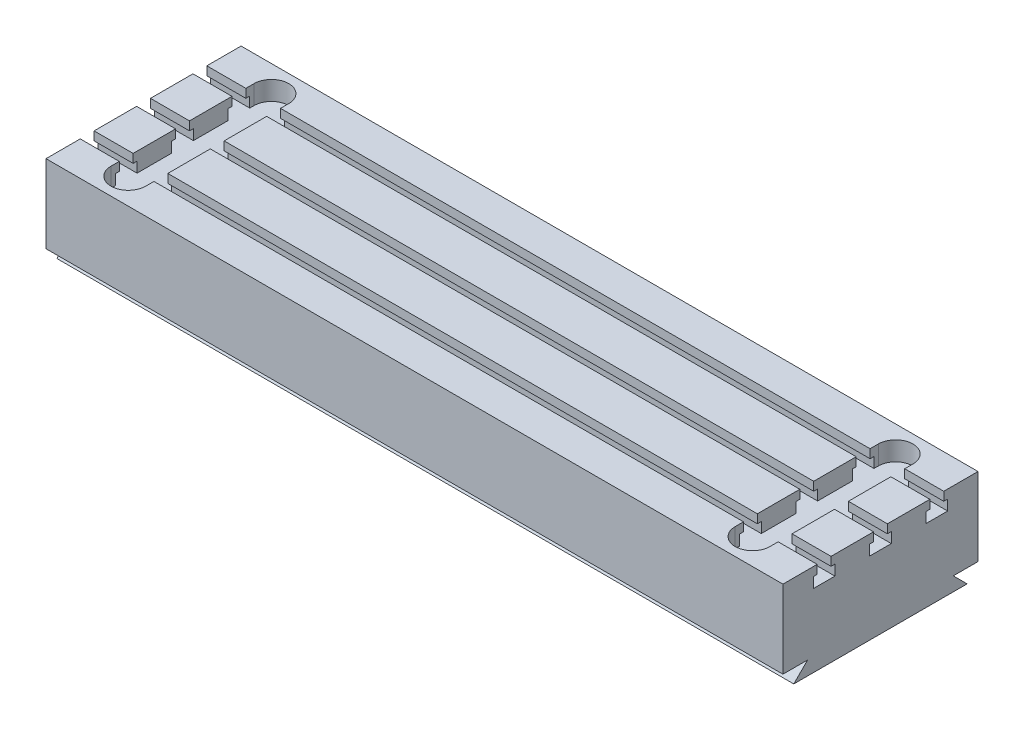
SolidWorks part; units mm, degrees
ref_plane "Front Plane" through (0, 0, 0) normal (0, 0, 1) x (1, 0, 0)
ref_plane "Top Plane" through (0, 0, 0) normal (0, 1, 0) x (1, 0, 0)
ref_plane "Right Plane" through (0, 0, 0) normal (1, 0, 0) x (0, 0, -1)
sketch "Sketch1" plane through (0, 0, 0) normal (1, 0, 0) x (0, 0, -1)
  line L0 (-84, -90) -> (-100, -106)
  line L1 (-112.5, 0) -> (-73, 0)
  line L2 (-112.5, 0) -> (-112.5, -90)
  line L3 (-112.5, -90) -> (-84, -90)
  line L4 (112.5, 0) -> (112.5, -90)
  line L5 (-100, -106) -> (100, -106)
  line L6 (100, -106) -> (84, -90)
  line L7 (84, -90) -> (112.5, -90)
  line L8 (-8, 0) -> (-8, -10)
  line L9 (-8, -10) -> (-12.5, -10)
  line L10 (-12.5, -10) -> (-12.5, -22)
  line L11 (-12.5, -22) -> (12.5, -22)
  line L12 (12.5, -22) -> (12.5, -10)
  line L13 (12.5, -10) -> (8, -10)
  line L14 (8, -10) -> (8, 0)
  line L15 (8, 0) -> (57, 0)
  line L16 (57, 0) -> (57, -10)
  line L17 (57, -10) -> (52.5, -10)
  line L18 (52.5, -10) -> (52.5, -22)
  line L19 (52.5, -22) -> (77.5, -22)
  line L20 (77.5, -22) -> (77.5, -10)
  line L21 (77.5, -10) -> (73, -10)
  line L22 (73, -10) -> (73, 0)
  line L23 (-73, 0) -> (-73, -10)
  line L24 (-73, -10) -> (-77.5, -10)
  line L25 (-77.5, -10) -> (-77.5, -22)
  line L26 (-77.5, -22) -> (-52.5, -22)
  line L27 (-52.5, -22) -> (-52.5, -10)
  line L28 (-52.5, -10) -> (-57, -10)
  line L29 (-57, -10) -> (-57, 0)
  line L30 (-57, 0) -> (-8, 0)
  line L31 (73, 0) -> (112.5, 0)
  point P6 (0, -22)
  point P10 (0, -106)
  point P37 (16.0009, 10.9669)
  dimension "D1" = 225
  dimension "D2" = 200
  dimension "D3" = 45
  dimension "D4" = 45
  dimension "D5" = 16
  dimension "D6" = 90
  dimension "D7" = 16
  dimension "D8" = 8
  dimension "D9" = 25
  dimension "D10" = 10
  dimension "D11" = 12
  dimension "D12" = 10
  dimension "D13" = 12
  dimension "D14" = 112.5
  dimension "D17" = 73
  dimension "D18" = 73
  dimension "D15" = 2
  dimension "D16" = 2
extrude "Boss-Extrude1" add sketch "Sketch1" along normal mid plane 850
sketch "Sketch2" plane through (0, 0, 0) normal (0, 1, 0) x (1, 0, 0)
  line L0 (340, -82.5) -> (340, 82.5)
  line L1 (380, 82.5) -> (380, -82.5)
  line L2 (425, 112.5) -> (425, 73) construction
  line L5 (-55, 0) -> (55, 0) construction
  line L6 (0, -55) -> (0, 55) construction
  line L7 (-380, 82.5) -> (-380, -82.5)
  line L8 (-340, -82.5) -> (-340, 82.5)
  arc A0 (340, 82.5) -> (380, 82.5) centre (360, 82.5) cw
  arc A1 (340, -82.5) -> (380, -82.5) centre (360, -82.5) ccw
  arc A2 (-340, -82.5) -> (-380, -82.5) centre (-360, -82.5) cw
  arc A3 (-340, 82.5) -> (-380, 82.5) centre (-360, 82.5) ccw
  point P10 (427.9354, 3.0721)
  dimension "D1" = 65
  dimension "D2" = 40
  dimension "D3" = 165
  dimension "D4" = 82.5
extrude "Cut-Extrude1" cut sketch "Sketch2" against normal blind 22
